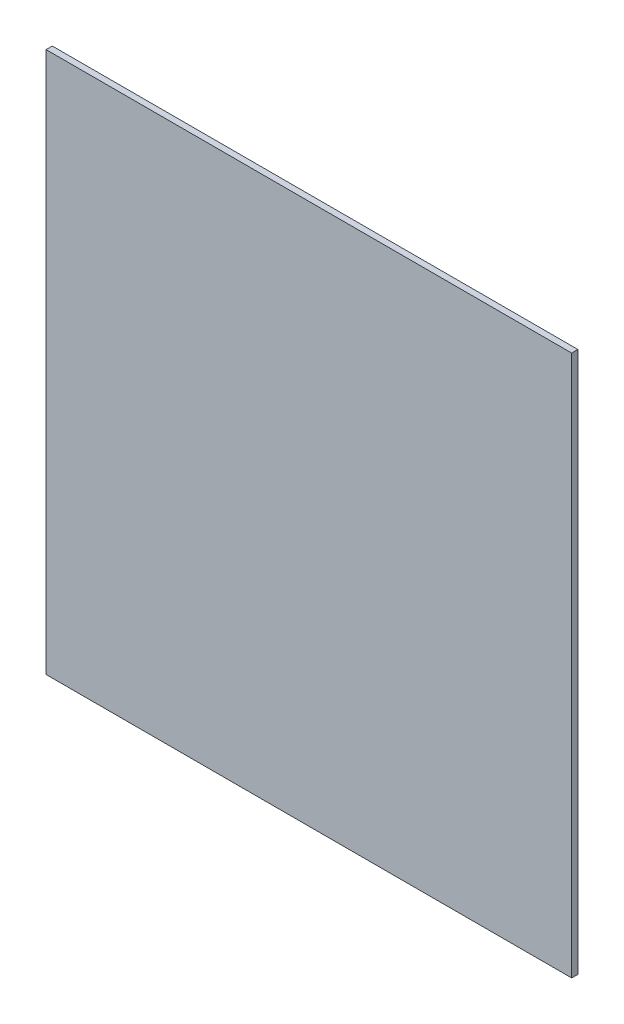
SolidWorks part; units mm, degrees
ref_plane "Plan de face" through (0, 0, 0) normal (0, 0, 1) x (1, 0, 0)
ref_plane "Plan de dessus" through (0, 0, 0) normal (0, 1, 0) x (1, 0, 0)
ref_plane "Plan de droite" through (0, 0, 0) normal (1, 0, 0) x (0, 0, -1)
sketch "Esquisse1" plane through (0, 0, 0) normal (0, 0, 1) x (1, 0, 0)
  line L1 (-169, -174) -> (169, -174)
  line L2 (-169, -174) -> (-169, 174)
  line L3 (-169, 174) -> (169, 174)
  line L4 (169, -174) -> (169, 174)
  line L5 (-169, -174) -> (169, 174) construction
  line L6 (-169, 174) -> (169, -174) construction
  point P0 (0, 0)
  dimension "D1" = 348
  dimension "D2" = 338
extrude "Boss.-Extru.1" add sketch "Esquisse1" along normal blind 4
sketch "Esquisse2" plane through (0, 0, 4) normal (0, 0, 1) x (1, 0, 0)
  line L0 (169, 174) -> (-169, 174) construction
  line L1 (-161, -166) -> (161, -166) construction
  line L2 (-161, -166) -> (-161, 166) construction
  line L3 (-161, 166) -> (161, 166) construction
  line L4 (161, -166) -> (161, 166) construction
  line L5 (-161, -166) -> (161, 166) construction
  line L6 (-161, 166) -> (161, -166) construction
  line L7 (-169, 174) -> (-169, -174) construction
  line L8 (169, -174) -> (169, 174) construction
  point P0 (19, 166)
  point P1 (-134, 166)
  point P2 (19, -166)
  point P3 (-134, -166)
  point P4 (0, 0)
  dimension "D1" = 8
  dimension "D2" = 8
  dimension "D3" = 35
  dimension "D4" = 150
hole_wizard "Dégagement M51" positions "Esquisse4" profile "Esquisse3" hole size "M5" standard "JIS"
sketch "Esquisse4" plane through (0, 0, 4) normal (0, 0, 1) x (1, 0, 0)
  point P0 (-140, -191.899)
  point P2 (-140, 191.9)
  point P4 (140, 188.1)
  point P6 (140, -191.9)
sketch "Esquisse3" plane through (-140, -191.899, 4) normal (1, 0, 0) x (0, -1, 0)
  line L0 (0, 0) -> (0, 4)
  line L1 (0, 4) -> (2.75, 4)
  line L2 (2.75, 4) -> (2.75, 0)
  line L5 (2.75, 0) -> (0, 0)
  line L11 (0, -6.35) -> (0, 107.95) construction
  dimension "Diamètre du perçage jusqu'au prochain" = 5.5
  dimension "Profondeur du perçage jusqu'au prochain" = 4
